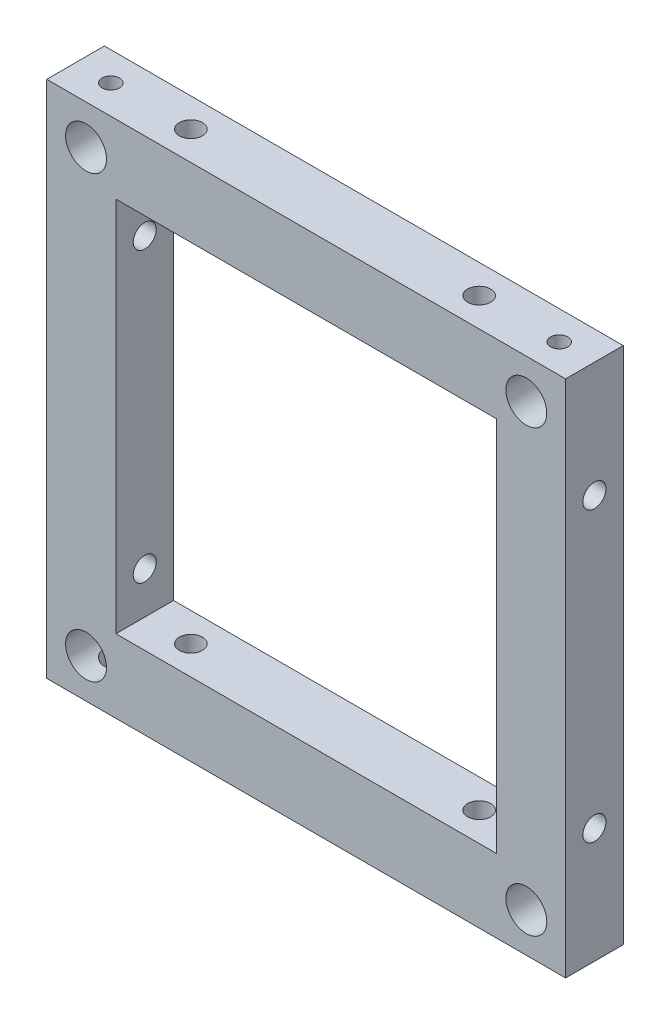
SolidWorks part; units mm, degrees
ref_plane "Front Plane" through (0, 0, 0) normal (0, 0, 1) x (1, 0, 0)
ref_plane "Top Plane" through (0, 0, 0) normal (0, 1, 0) x (1, 0, 0)
ref_plane "Right Plane" through (0, 0, 0) normal (1, 0, 0) x (0, 0, -1)
sketch "Sketch1" plane through (0, 0, 0) normal (0, 0, 1) x (1, 0, 0)
  line L0 (0, 45) -> (0, 0) construction
  line L1 (45, 45) -> (-45, 45)
  line L2 (45, 45) -> (45, -45)
  line L3 (45, -45) -> (-45, -45)
  line L4 (-45, 45) -> (-45, -45)
  line L5 (0, 0) -> (45, 0) construction
  line L7 (33, -32.2908) -> (-33, -32.2908)
  line L8 (33, -32.2908) -> (33, 33)
  line L9 (33, 33) -> (-33, 33)
  line L10 (-33, -32.2908) -> (-33, 33)
  line L13 (-38.185, -38.1875) -> (38.185, -38.1875) construction
  line L14 (-38.185, -38.1875) -> (-38.185, 38.1825) construction
  line L15 (-38.185, 38.1825) -> (38.185, 38.1825) construction
  line L16 (38.185, -38.1875) -> (38.185, 38.1825) construction
  circle A0 centre (-38.185, 38.1825) radius 3.55
  circle A1 centre (38.185, 38.1825) radius 3.55
  circle A2 centre (38.185, -38.1825) radius 3.55
  circle A3 centre (-38.185, -38.1825) radius 3.55
  point P0 (0, 0)
  point P6 (0, 0)
  point P11 (45, 0)
  point P12 (0, 0)
  dimension "D7" = 7.1
  dimension "D8" = 54
  dimension "D1" = 90
  dimension "D2" = 90
  dimension "D3" = 12
  dimension "D4" = 12
  dimension "D5" = 76.37
  dimension "D6" = 76.37
  dimension "D9" = 33
  dimension "D10" = 5.8917
extrude "Boss-Extrude1" add sketch "Sketch1" along normal blind 10
sketch "Sketch2" plane through (0, -45, 0) normal (0, -1, 0) x (1, 0, 0)
  line L0 (-45, 5) -> (45, 5) construction
  line L1 (-45, 10) -> (-45, 0) construction
  line L2 (45, 10) -> (45, 0) construction
  line L3 (0, 0) -> (0, 10) construction
  line L4 (-45, 10) -> (45, 10) construction
  circle A0 centre (-38.89, 5) radius 1.5
  circle A1 centre (38.89, 5) radius 1.5
  dimension "D1" = 77.78
  dimension "D2" = 3
extrude "Cut-Extrude1" cut sketch "Sketch2" against normal up to next
mirror "Mirror1" about plane through (0, 0, 0) normal (0, 1, 0) of "Cut-Extrude1"
sketch "Sketch3" plane through (0, -45, 0) normal (0, -1, 0) x (1, 0, 0)
  line L0 (-45, 5) -> (45, 5) construction
  line L1 (-45, 10) -> (-45, 0) construction
  line L2 (45, 10) -> (45, 0) construction
  line L3 (0, 0) -> (0, 10) construction
  line L4 (-45, 10) -> (45, 10) construction
  circle A0 centre (-25, 5) radius 2
  circle A1 centre (25, 5) radius 2
  dimension "D1" = 50
  dimension "D2" = 4
extrude "Cut-Extrude2" cut sketch "Sketch3" against normal blind 90
sketch "Sketch4" plane through (-45, 0, 0) normal (-1, 0, 0) x (0, 0, 1)
  line L0 (5, 45) -> (5, -45) construction
  line L1 (10, 45) -> (0, 45) construction
  line L2 (10, -45) -> (0, -45) construction
  line L3 (0, 0) -> (10, 0) construction
  line L4 (0, 45) -> (0, -45) construction
  line L5 (10, 45) -> (10, -45) construction
  circle A0 centre (5, 25) radius 2
  circle A1 centre (5, -25) radius 2
  dimension "D1" = 50
  dimension "D2" = 4
extrude "Cut-Extrude3" cut sketch "Sketch4" against normal blind 90
